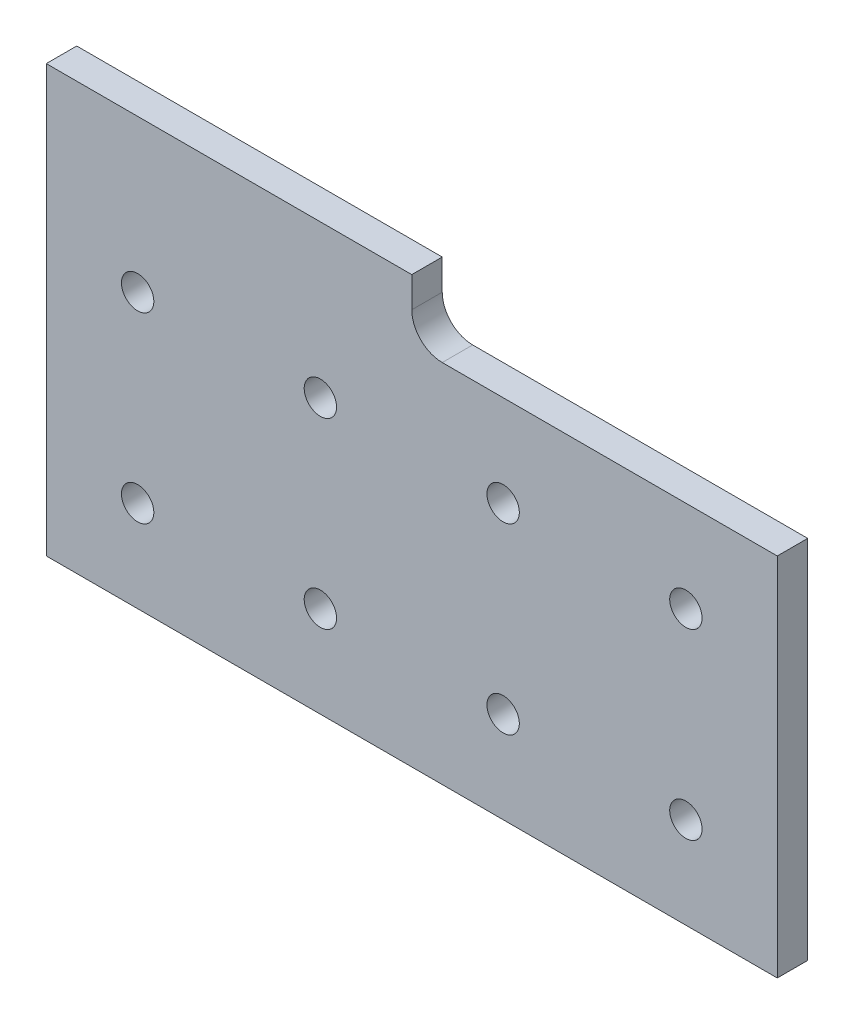
SolidWorks part; units mm, degrees
material "6061-T6 (SS)"
ref_plane "Front" through (0, 0, 0) normal (0, 0, 1) x (1, 0, 0)
ref_plane "Top" through (0, 0, 0) normal (0, 1, 0) x (1, 0, 0)
ref_plane "Right" through (0, 0, 0) normal (1, 0, 0) x (0, 0, -1)
sketch "Sketch1" plane through (0, 0, 0) normal (0, 0, 1) x (1, 0, 0)
  line L0 (0, 0) -> (152.4, 0)
  line L1 (152.4, 0) -> (152.4, 88.9)
  line L2 (152.4, 88.9) -> (0, 88.9)
  line L3 (0, 88.9) -> (0, 0)
  dimension "D1" = 152.4
  dimension "D2" = 88.9
extrude "Boss-Extrude1" add sketch "Sketch1" along normal blind 6.35
hole_wizard "17/64 (0.26563) Diameter Hole1" positions "Sketch2" profile "Sketch3" hole size "17/64" standard "ANSI Inch" end condition through all
sketch "Sketch2" plane through (0, 0, 6.35) normal (0, 0, 1) x (1, 0, 0)
  line L0 (0, 88.9) -> (0, 0) construction
  line L1 (0, 0) -> (152.4, 0) construction
  point P0 (19.05, 19.05)
  dimension "D1" = 19.05
  dimension "D2" = 19.05
sketch "Sketch3" plane through (19.05, 19.05, 6.35) normal (1, 0, 0) x (0, -1, 0)
  line L0 (0, 0) -> (0, 6.35)
  line L1 (0, 6.35) -> (3.3735, 6.35)
  line L2 (3.3735, 6.35) -> (3.3735, 0)
  line L5 (3.3735, 0) -> (0, 0)
  line L11 (0, -6.35) -> (0, 107.95) construction
  dimension "Thru Hole Dia." = 6.747
  dimension "Thru Hole Depth" = 6.35
pattern_linear "LPattern1" count 4 spacing 38.1 along (1, 0, 0) count 2 spacing 38.1 along (0, 1, 0) of "17/64 (0.26563) Diameter Hole1"
sketch "Sketch4" plane through (0, 0, 6.35) normal (0, 0, 1) x (1, 0, 0)
  line L0 (152.4, 0) -> (152.4, 88.9) construction
  line L1 (76.2, 88.9) -> (152.4, 88.9)
  line L2 (76.2, 88.9) -> (76.2, 76.2)
  line L3 (76.2, 76.2) -> (152.4, 76.2)
  line L4 (152.4, 88.9) -> (152.4, 76.2)
  line L5 (152.4, 88.9) -> (0, 88.9) construction
  dimension "D1" = 76.2
  dimension "D2" = 0
  dimension "D3" = 0
  dimension "D4" = 12.7
extrude "Cut-Extrude1" cut sketch "Sketch4" against normal through all
fillet "Fillet1" radius 6.35 1 edges at (76.2, 76.2, 3.175)
